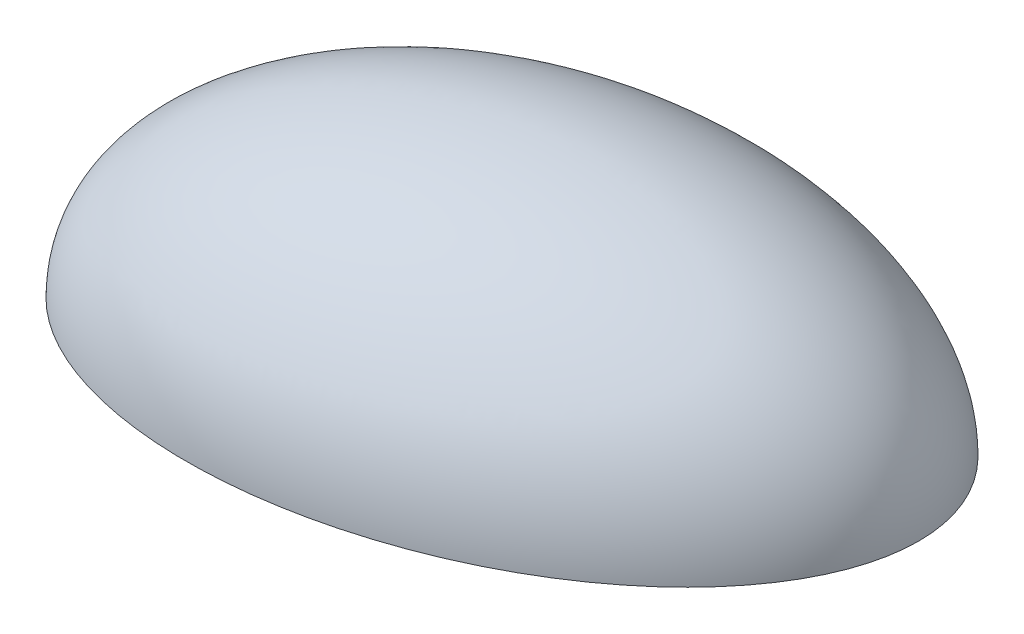
SolidWorks part; units mm, degrees
ref_plane "Plan de face" through (0, 0, 0) normal (0, 0, 1) x (1, 0, 0)
ref_plane "Plan de dessus" through (0, 0, 0) normal (0, 1, 0) x (1, 0, 0)
ref_plane "Plan de droite" through (0, 0, 0) normal (1, 0, 0) x (0, 0, -1)
sketch "Esquisse1" plane through (0, 0, 0) normal (0, 1, 0) x (1, 0, 0)
  line L0 (-19.1389, -5.8055) -> (19.1389, 5.8055) construction
  line L1 (-16.268, -4.9346) -> (-19.1389, -5.8055)
  line L2 (16.268, 4.9346) -> (19.1389, 5.8055)
  ellipse E0 centre (0, 0) end of major axis (19.1389, 5.8055) minor radius 12.5 (19.1389, 5.8055) -> (-19.1389, -5.8055) ccw
  ellipse E1 centre (0, 0) end of major axis (16.268, 4.9346) minor radius 9.5 (16.268, 4.9346) -> (-16.268, -4.9346) ccw
  dimension "D1" = 20
  dimension "D2" = 12.5
  dimension "D3" = 3
  dimension "D4" = 3
revolve "Révolution1" add sketch "Esquisse1" angle 180 about L0
